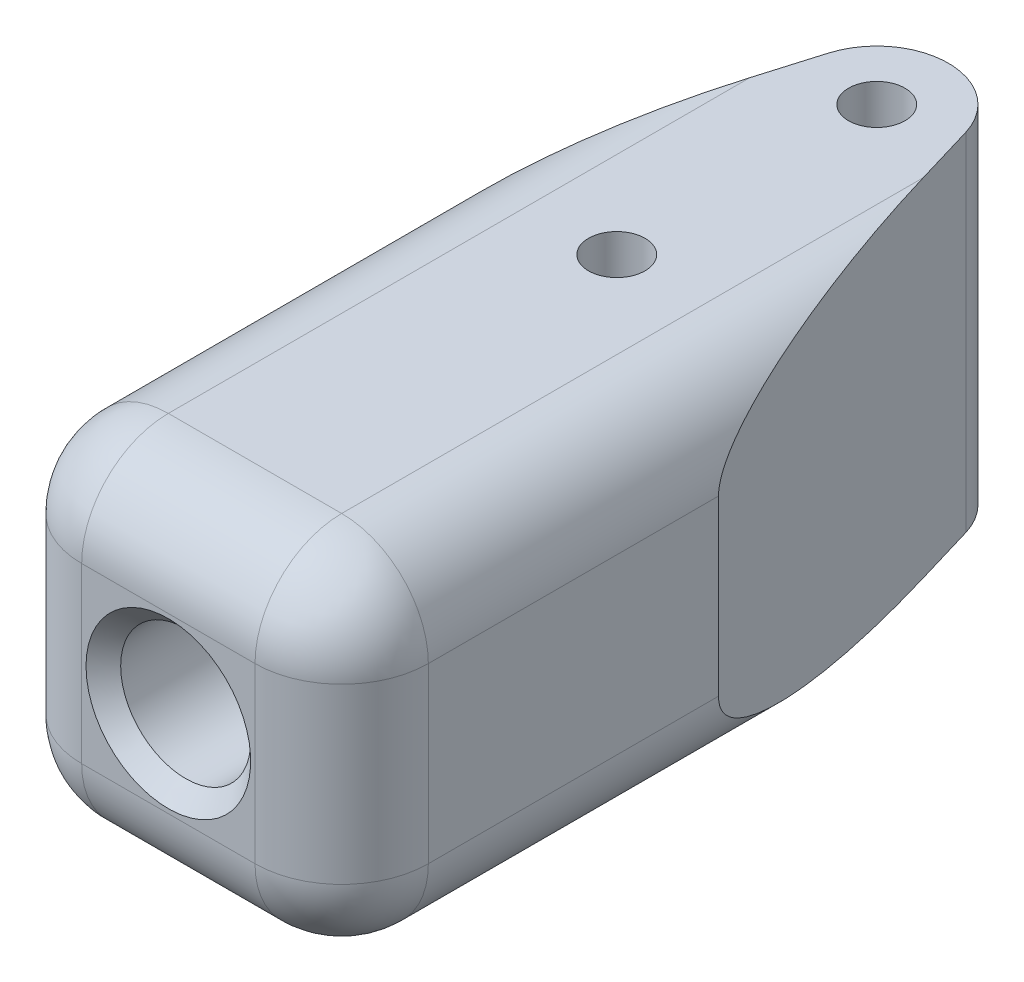
SolidWorks part; units mm, degrees
material "ABS"
ref_plane "Front Plane" through (0, 0, 0) normal (0, 0, 1) x (1, 0, 0)
ref_plane "Top Plane" through (0, 0, 0) normal (0, 1, 0) x (1, 0, 0)
ref_plane "Right Plane" through (0, 0, 0) normal (1, 0, 0) x (0, 0, -1)
sketch "Sketch1" plane through (0, 0, 0) normal (0, 0, 1) x (1, 0, 0)
  line L1 (12.7, 12.7) -> (-12.7, 12.7)
  line L2 (12.7, 12.7) -> (12.7, -12.7)
  line L3 (12.7, -12.7) -> (-12.7, -12.7)
  line L4 (-12.7, 12.7) -> (-12.7, -12.7)
  line L5 (12.7, 12.7) -> (-12.7, -12.7) construction
  line L6 (12.7, -12.7) -> (-12.7, 12.7) construction
  circle A0 centre (0, 0) radius 4.7625 construction
  dimension "D1" = 9.525
  dimension "D2" = 25.4
  dimension "D3" = 25.4
extrude "Boss-Extrude1" add sketch "Sketch1" along normal blind 57.15
sketch "Sketch2" plane through (0, 12.7, 0) normal (0, 1, 0) x (1, 0, 0)
  line L0 (0, 0) -> (0, -57.15) construction
  line L1 (12.7, -57.15) -> (-12.7, -57.15) construction
  line L2 (12.7, 0) -> (-12.7, 0) construction
  line L3 (-12.7, -29.5402) -> (12.7, -29.5402)
  line L4 (4.7625, -82.55) -> (-4.7625, -82.55) construction
  line L5 (4.7625, -82.55) -> (4.7625, -31.75) construction
  line L6 (4.7625, -31.75) -> (-4.7625, -31.75) construction
  line L7 (-4.7625, -82.55) -> (-4.7625, -31.75) construction
  line L8 (4.7625, -82.55) -> (-4.7625, -31.75) construction
  line L9 (4.7625, -31.75) -> (-4.7625, -82.55) construction
  line L10 (-12.7, -57.15) -> (-12.7, 0) construction
  line L11 (12.7, -57.15) -> (12.7, 0) construction
  line L12 (-12.7, -29.5402) -> (-5.0273, -3.7495)
  line L13 (12.7, -29.5402) -> (5.0273, -3.7495)
  line L14 (-12.7, -29.5402) -> (-12.7, 0)
  line L15 (12.7, 0) -> (-12.7, 0)
  line L16 (12.7, -29.5402) -> (12.7, 0)
  circle A0 centre (0, -5.2451) radius 2.0701
  circle A1 centre (0, -24.2951) radius 2.0701
  arc A2 (5.0273, -3.7495) -> (-5.0273, -3.7495) centre (0, -5.2451) ccw
  circle A3 centre (0, -24.2951) radius 5.2451 construction
  line M3 (12.7, 0) -> (-12.7, 0)
  line M4 (-12.7, 0) -> (-12.7, -57.15)
  line M6 (12.7, -57.15) -> (12.7, 0)
  dimension "D1" = 4.1402
  dimension "D2" = 3.175
  dimension "D3" = 19.05
  dimension "D4" = 9.525
  dimension "D5" = 50.8
extrude "Cut-Extrude1" cut sketch "Sketch2" against normal through all and the other way through all contours A2 L13 M6 M3 | A1 | A0 | A2 L15 L12 M4 | L3
sketch "Sketch4" plane through (0, 0, 57.15) normal (0, 0, 1) x (1, 0, 0)
  circle A0 centre (0, 0) radius 4.7625
  dimension "D1" = 9.525
extrude "Cut-Extrude2" cut sketch "Sketch4" against normal blind 25.4
chamfer "Chamfer1" distance 1.27 angle 45 1 edges at (4.7625, 0, 57.15)
fillet "Fillet1" radius 6.35 5 edges at (-12.7, -12.7, 43.3451) (12.7, -12.7, 43.3451) (0, -12.7, 57.15) (-12.7, 0, 57.15) (12.7, 0, 57.15)
fillet "Fillet2" radius 6.35 5 edges at (12.7, 12.7, 40.1701) (10.8401, 12.7, 55.2901) (0, 12.7, 57.15) (-10.8401, 12.7, 55.2901) (-12.7, 12.7, 40.1701)
